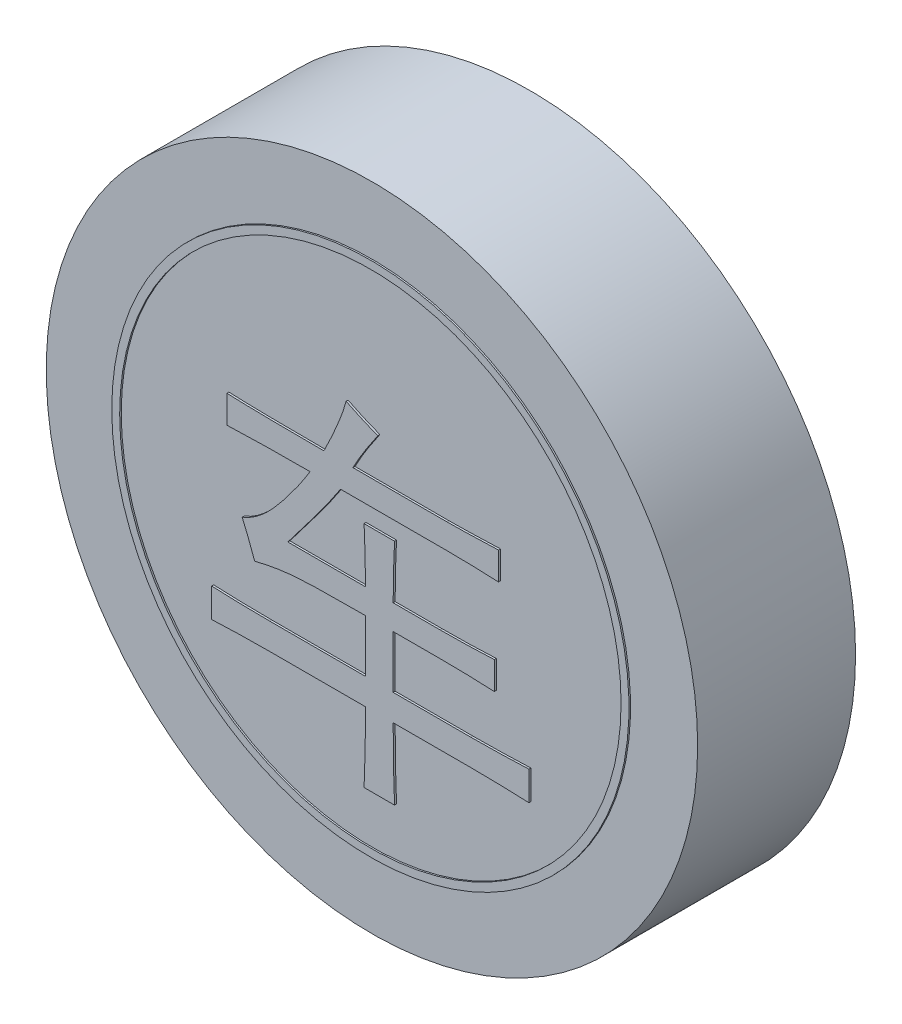
SolidWorks part; units mm, degrees
ref_plane "前视基准面" through (0, 0, 0) normal (0, 0, 1) x (1, 0, 0)
ref_plane "上视基准面" through (0, 0, 0) normal (0, 1, 0) x (1, 0, 0)
ref_plane "右视基准面" through (0, 0, 0) normal (1, 0, 0) x (0, 0, -1)
other "Configuration Table"
sketch "草图1" plane through (0, 0, 0) normal (0, 0, 1) x (1, 0, 0)
  circle A0 centre (0, 0) radius 16.5
  dimension "D1" = 33
extrude "Diameter33_Height8" add sketch "草图1" against normal blind 8
sketch "草图2" plane through (0, 0, 0) normal (0, 0, 1) x (1, 0, 0)
  text T0 "车" font "SimHei" height 12
extrude "Character_车" add sketch "草图2" along normal blind 0.1
sketch "草图3" plane through (0, 0, 0) normal (0, 0, 1) x (1, 0, 0)
  circle A0 centre (0, 0) radius 13.1
  circle A1 centre (0, 0) radius 12.7
extrude "Ink_ring" add sketch "草图3" along normal blind 0.08
